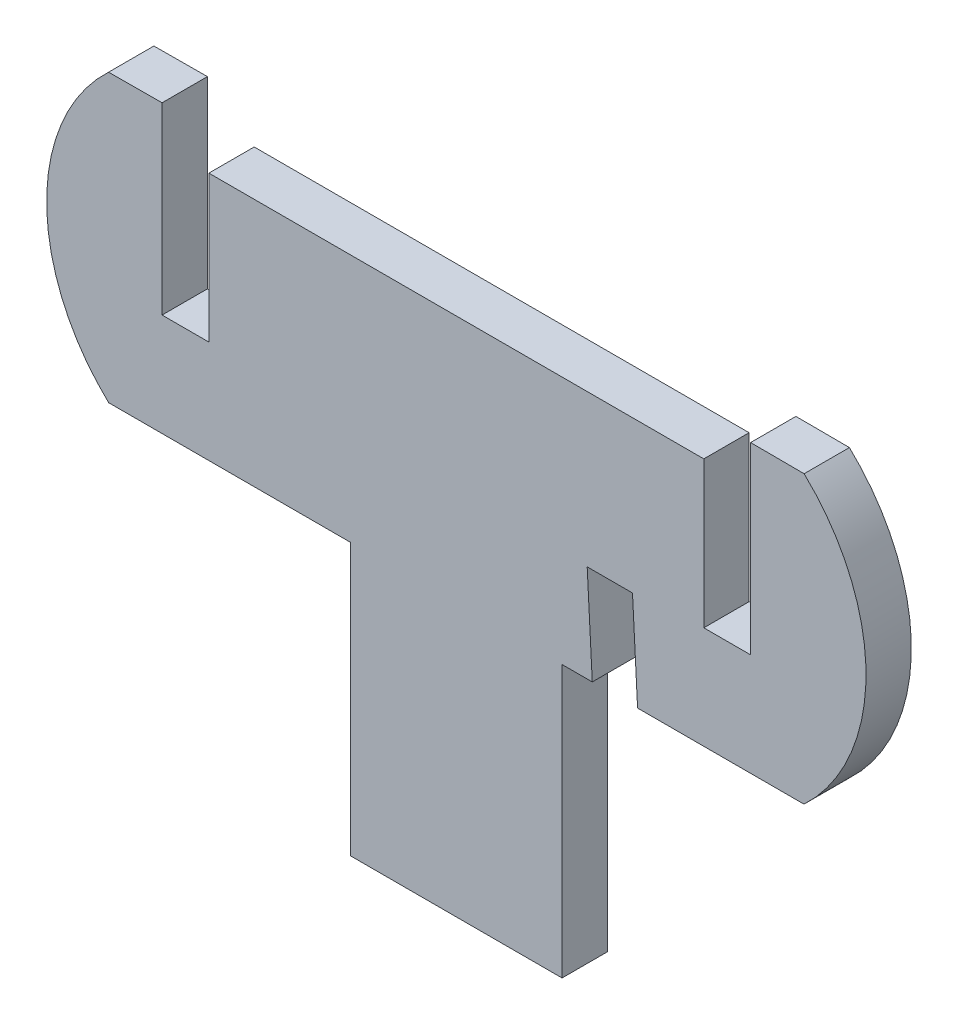
SolidWorks part; units mm, degrees
ref_plane "Front" through (0, 0, 0) normal (0, 0, 1) x (1, 0, 0)
ref_plane "Top" through (0, 0, 0) normal (0, 1, 0) x (1, 0, 0)
ref_plane "Right" through (0, 0, 0) normal (1, 0, 0) x (0, 0, -1)
sketch "Sketch1" plane through (0, 0, 0) normal (0, 0, 1) x (1, 0, 0)
  line L2 (457.2875, -79.2146) -> (453.7454, -79.2305)
  line L3 (460.3866, -91.3872) -> (457.2875, -91.3872)
  line L4 (453.754, -98.183) -> (469.7716, -98.183)
  line L5 (483.7716, -116.1598) -> (483.7716, -98.183)
  line L8 (488.4345, -91.7511) -> (485.4345, -91.7511)
  line L9 (457.2875, -91.3872) -> (457.2875, -79.2146)
  line L10 (460.3866, -81.699) -> (460.3866, -91.3872)
  line L12 (485.4345, -91.7511) -> (485.7716, -98.183)
  line L14 (485.7716, -98.183) -> (483.7716, -98.183)
  line L16 (469.7653, -116.1598) -> (483.7716, -116.1598)
  line L17 (488.4345, -91.7511) -> (488.7716, -98.183)
  line L18 (493.1566, -81.699) -> (460.3866, -81.699)
  line L20 (493.1566, -81.699) -> (493.1566, -91.3872)
  line L21 (496.2556, -91.3872) -> (496.2556, -79.2146)
  line L24 (499.7891, -98.183) -> (488.7716, -98.183)
  line L25 (493.1566, -91.3872) -> (496.2556, -91.3872)
  line L26 (469.7653, -116.1598) -> (469.7716, -98.183)
  line L27 (496.2556, -79.2146) -> (499.7977, -79.2305)
  line L29 (476.7716, -81.699) -> (476.7716, -116.1598) construction
  arc A0 (453.754, -98.183) -> (453.7454, -79.2305) centre (462.6392, -88.7027) cw
  arc A1 (499.7891, -98.183) -> (499.7977, -79.2305) centre (490.904, -88.7027) ccw
  point P34 (444.5916, -85.6193)
  point P35 (444.5632, -79.2717)
  dimension "D1" = 32.77
  dimension "D2" = 3
  dimension "D3" = 3
  dimension "D6" = 34.4609
  dimension "D7" = 7
  dimension "D8" = 93
  dimension "D9" = 2
extrude "Base-Extrude" add sketch "Sketch1" along normal blind 3
